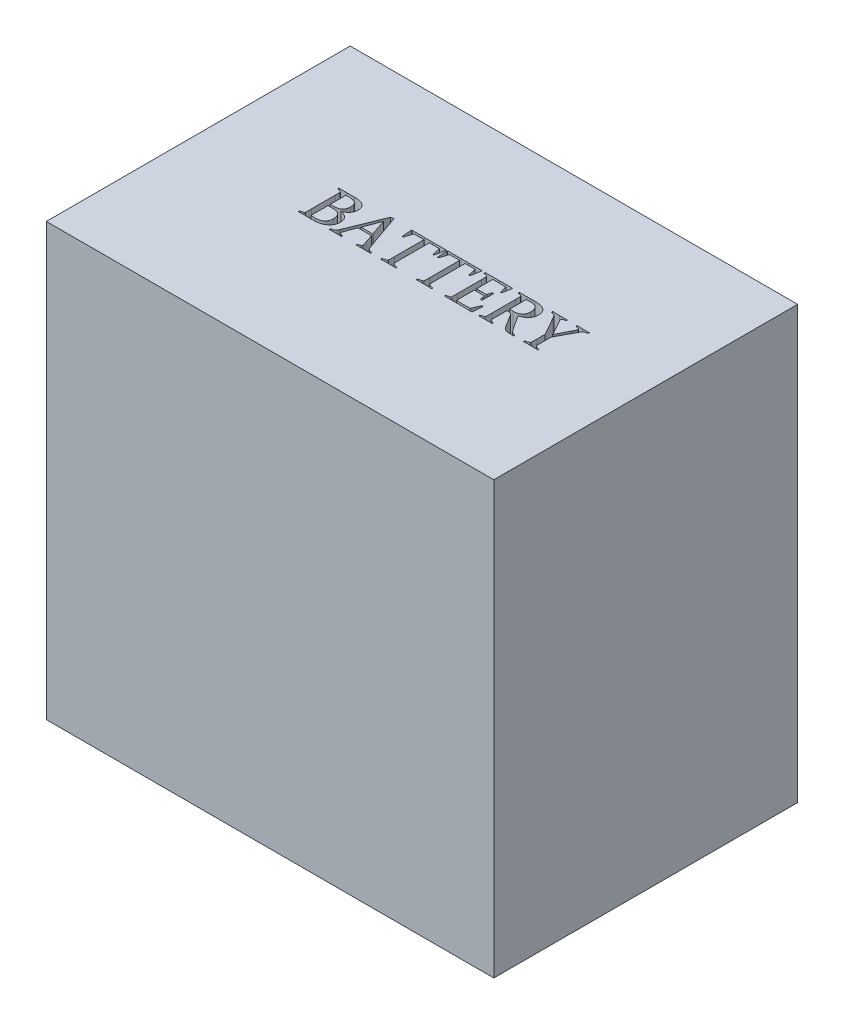
SolidWorks part; units mm, degrees
ref_plane "Front Plane" through (0, 0, 0) normal (0, 0, 1) x (1, 0, 0)
ref_plane "Top Plane" through (0, 0, 0) normal (0, 1, 0) x (1, 0, 0)
ref_plane "Right Plane" through (0, 0, 0) normal (1, 0, 0) x (0, 0, -1)
sketch "Sketch1" plane through (0, 0, 0) normal (0, 1, 0) x (1, 0, 0)
  line L1 (-104.5249, 1.7342) -> (35.4751, 1.7342)
  line L2 (-104.5249, 1.7342) -> (-104.5249, -93.3258)
  line L3 (-104.5249, -93.3258) -> (35.4751, -93.3258)
  line L4 (35.4751, 1.7342) -> (35.4751, -93.3258)
  dimension "D1" = 95.06
  dimension "D2" = 140
extrude "Boss-Extrude1" add sketch "Sketch1" along normal blind 135
sketch "Sketch3" plane through (0, 135, 0) normal (0, 1, 0) x (1, 0, 0)
  text T0 "BATTERY" font "Constantia" height in points 48
extrude "Cut-Extrude1" cut sketch "Sketch3" against normal blind 10
equation "\"3.94inch\"=10"
